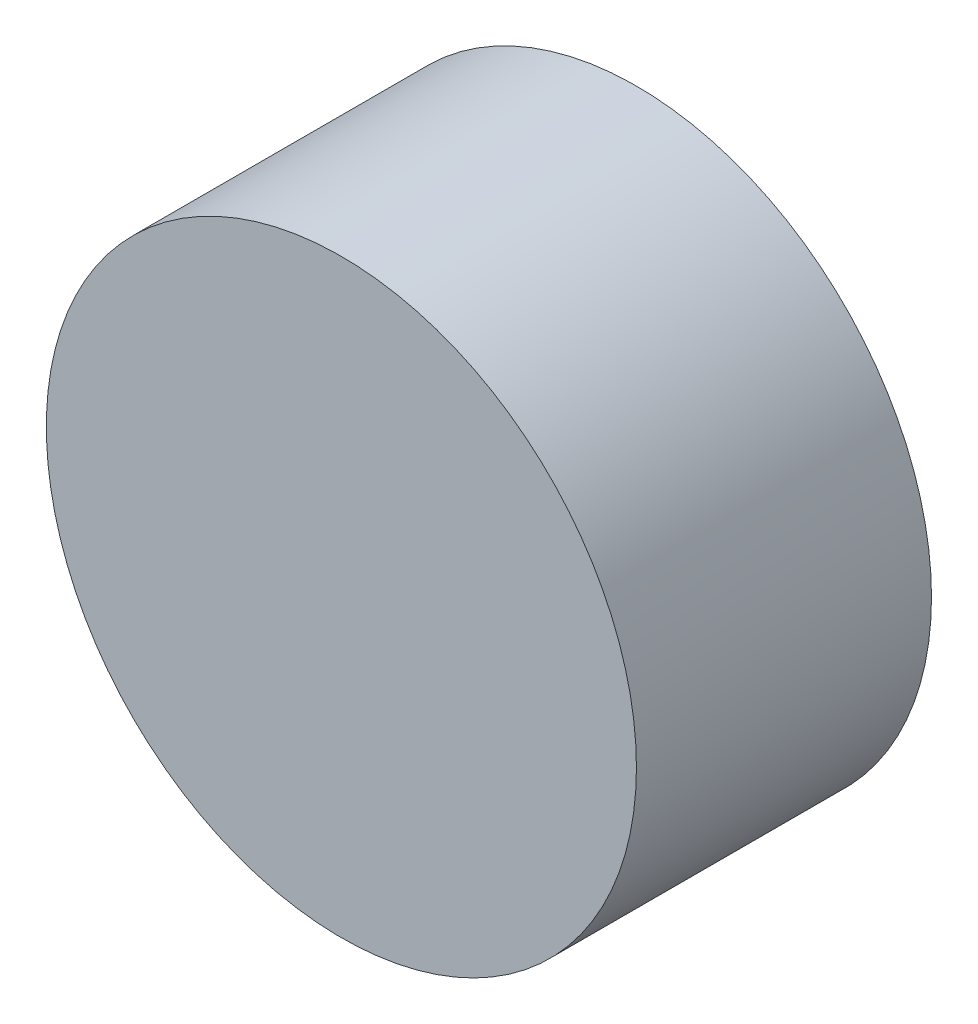
SolidWorks part; units mm, degrees
material "Titanium"
ref_plane "Front Plane" through (0, 0, 0) normal (0, 0, 1) x (1, 0, 0)
ref_plane "Top Plane" through (0, 0, 0) normal (0, 1, 0) x (1, 0, 0)
ref_plane "Right Plane" through (0, 0, 0) normal (1, 0, 0) x (0, 0, -1)
sketch "Sketch1" plane through (0, 0, 0) normal (0, 0, 1) x (1, 0, 0)
  circle A0 centre (0, 0) radius 5
  dimension "D1" = 10
extrude "Boss-Extrude1" add sketch "Sketch1" along normal blind 5
